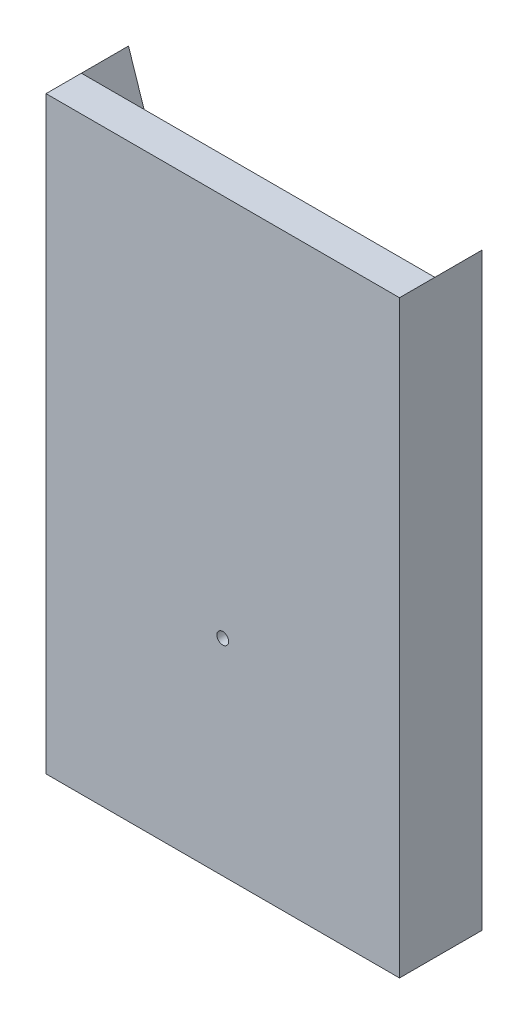
SolidWorks part; units mm, degrees
ref_plane "Спереди" through (0, 0, 0) normal (0, 0, 1) x (1, 0, 0)
ref_plane "Сверху" through (0, 0, 0) normal (0, 1, 0) x (1, 0, 0)
ref_plane "Справа" through (0, 0, 0) normal (1, 0, 0) x (0, 0, -1)
sketch "Эскиз1" plane through (0, 0, 0) normal (0, 0, 1) x (1, 0, 0)
  line L1 (0, 0) -> (150, 0)
  line L2 (0, 0) -> (0, -250)
  line L3 (0, -250) -> (150, -250)
  line L4 (150, 0) -> (150, -250)
  dimension "D1" = 150
  dimension "D2" = 250
extrude "Бобышка-Вытянуть1" add sketch "Эскиз1" along normal blind 35
sketch "Эскиз2" plane through (0, 0, 0) normal (0, 0, 1) x (1, 0, 0)
  line L0 (75, 0) -> (75, -250) construction
  line L1 (150, 0) -> (0, 0) construction
  line L2 (0, -250) -> (150, -250) construction
  line L3 (0, 0) -> (44.9946, -136.1852)
  line L4 (44.9946, -189.088) -> (0, -250)
  line L5 (105.0054, -189.088) -> (150, -250)
  line L6 (150, 0) -> (105.0054, -136.1852)
  line L7 (0, 0) -> (150, 0)
  line L8 (0, -250) -> (150, -250)
  arc A0 (44.9946, -136.1852) -> (44.9946, -189.088) centre (75, -162.6366) ccw
  arc A1 (105.0054, -189.088) -> (105.0054, -136.1852) centre (75, -162.6366) ccw
  dimension "D1" = 80
extrude "Вырез-Вытянуть1" cut sketch "Эскиз2" along normal blind 20
sketch "Эскиз3" plane through (0, 0, 20) normal (0, 0, -1) x (-1, 0, 0)
  line L0 (-75, -250) -> (-75, 0) construction
  line L1 (0, -250) -> (-150, -250) construction
  line L2 (-150, 0) -> (0, 0) construction
  circle A0 centre (-75, -162.6366) radius 2.5
extrude "Вырез-Вытянуть2" cut sketch "Эскиз3" against normal through all
